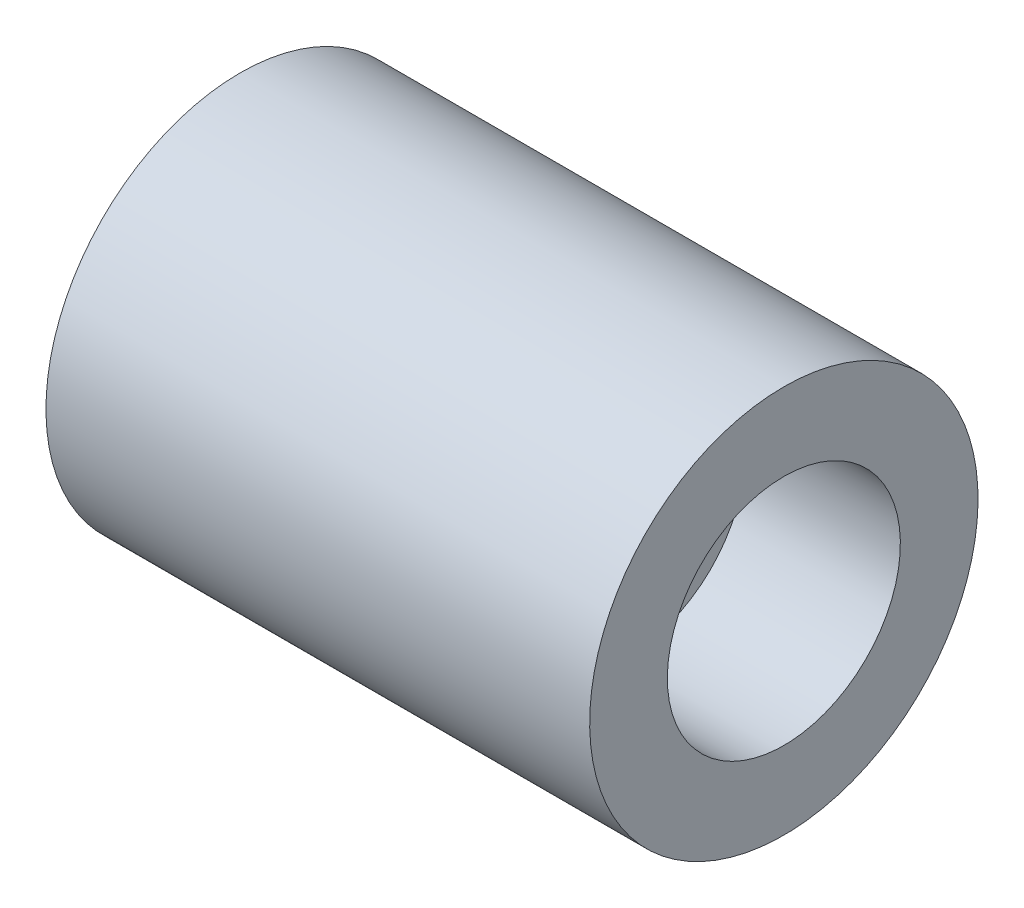
SolidWorks part; units mm, degrees
ref_plane "Alzado" through (0, 0, 0) normal (0, 0, 1) x (1, 0, 0)
ref_plane "Planta" through (0, 0, 0) normal (0, 1, 0) x (1, 0, 0)
ref_plane "Vista lateral" through (0, 0, 0) normal (1, 0, 0) x (0, 0, -1)
sketch "Croquis1" plane through (0, 0, 0) normal (0, 0, 1) x (1, 0, 0)
  line L0 (0, 0) -> (0, 50)
  line L1 (0, 50) -> (140, 50)
  line L2 (140, 50) -> (140, 30)
  line L3 (140, 30) -> (100, 30)
  line L4 (100, 30) -> (100, 10)
  line L5 (100, 10) -> (20, 10)
  line L6 (20, 10) -> (20, 0)
  line L7 (20, 0) -> (0, 0)
  dimension "D1" = 50
  dimension "D2" = 10
  dimension "D3" = 30
  dimension "D4" = 40
  dimension "D5" = 120
  dimension "D6" = 140
revolve "Revolución1" add sketch "Croquis1" angle 360 about L7
equation "\"A\"= 10"
equation "\"D1@Croquis1\"=\"A\"*5"
equation "\"D2@Croquis1\"=\"A\""
equation "\"D3@Croquis1\"=\"A\"*3"
equation "\"D4@Croquis1\"=\"D1@Croquis1\"-\"A\""
equation "\"D5@Croquis1\"=\"D4@Croquis1\"*3"
equation "\"D6@Croquis1\"=\"D5@Croquis1\"+20"
